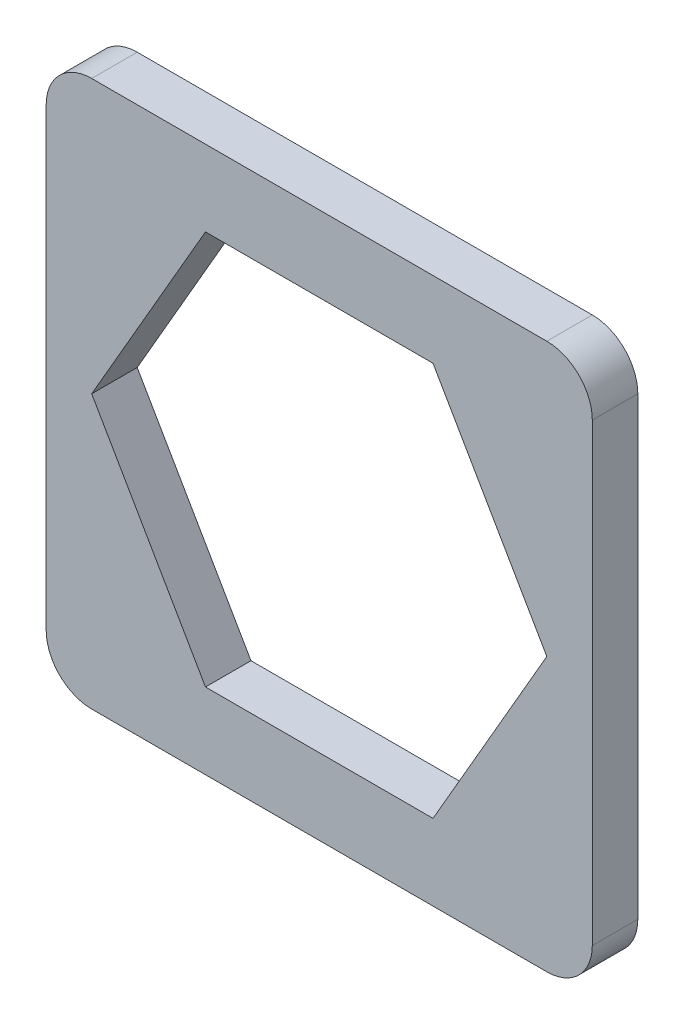
SolidWorks part; units mm, degrees
ref_plane "Front Plane" through (0, 0, 0) normal (0, 0, 1) x (1, 0, 0)
ref_plane "Top Plane" through (0, 0, 0) normal (0, 1, 0) x (1, 0, 0)
ref_plane "Right Plane" through (0, 0, 0) normal (1, 0, 0) x (0, 0, -1)
sketch "Sketch1" plane through (0, 0, 0) normal (0, 0, 1) x (1, 0, 0)
  line L1 (-50, 60) -> (50, 60)
  line L2 (-60, 50) -> (-60, -50)
  line L3 (-50, -60) -> (50, -60)
  line L4 (60, 50) -> (60, -50)
  line L5 (-60, 60) -> (60, -60) construction
  line L6 (-60, -60) -> (60, 60) construction
  arc A0 (-60, -50) -> (-50, -60) centre (-50, -50) ccw
  arc A1 (50, -60) -> (60, -50) centre (50, -50) ccw
  arc A2 (50, 60) -> (60, 50) centre (50, 50) cw
  arc A3 (-50, 60) -> (-60, 50) centre (-50, 50) ccw
  point P0 (0, 0)
  dimension "D3" = 10
  dimension "D1" = 120
  dimension "D2" = 120
extrude "Boss-Extrude1" add sketch "Sketch1" along normal blind 10 contours A3 L2 A0 L3 A1 L4 A2 L1
sketch "Sketch2" plane through (0, 0, 10) normal (0, 0, 1) x (1, 0, 0)
  line L0 (0, 0) -> (0, 40) construction
  line L1 (-50, 50) -> (50, 50) construction
  line L2 (-50, 50) -> (-50, -50) construction
  line L3 (-50, -50) -> (50, -50) construction
  line L4 (50, 50) -> (50, -50) construction
  line L5 (-50, 50) -> (50, -50) construction
  line L6 (-50, -50) -> (50, 50) construction
  line L7 (0, 40) -> (-40, 40) construction
  line L8 (-40, 40) -> (-40, 0) construction
  line L9 (-40, 0) -> (0, 0) construction
  line L11 (0, 20) -> (-20, 20) construction
  line L12 (-20, 40) -> (-20, 20) construction
  circle A0 centre (0, 40) radius 4 construction
  circle A1 centre (0, 20) radius 4 construction
  circle A2 centre (0, 0) radius 4 construction
  circle A3 centre (-20, 20) radius 4 construction
  circle A4 centre (-20, 40) radius 4 construction
  circle A5 centre (-40, 40) radius 4 construction
  circle A6 centre (0, 0) radius 4 construction
  circle A7 centre (20, 0) radius 4 construction
  circle A8 centre (40, 0) radius 4 construction
  circle A9 centre (40, 20) radius 4 construction
  circle A10 centre (40, 40) radius 4 construction
  circle A11 centre (20, 20) radius 4 construction
  circle A12 centre (0, 0) radius 4 construction
  circle A13 centre (0, -20) radius 4 construction
  circle A14 centre (0, -40) radius 4 construction
  circle A15 centre (20, -40) radius 4 construction
  circle A16 centre (40, -40) radius 4 construction
  circle A17 centre (20, -20) radius 4 construction
  circle A18 centre (0, 0) radius 4
  circle A19 centre (-20, 0) radius 4 construction
  circle A20 centre (-40, 0) radius 4 construction
  circle A21 centre (-40, -20) radius 4 construction
  circle A22 centre (-40, -40) radius 4 construction
  circle A23 centre (-20, -20) radius 4 construction
  point P0 (0, 0)
  point P55 (0, 0)
  dimension "D4" = 8
  dimension "D1" = 100
  dimension "D2" = 100
  dimension "D3" = 40
  dimension "D5" = 4
sketch "Sketch3" plane through (0, 0, 10) normal (0, 0, 1) x (1, 0, 0)
  line L0 (-50, -50) -> (50, -50) construction
  line L1 (25, -43.3013) -> (50, 0)
  line L2 (50, 0) -> (25, 43.3013)
  line L3 (25, 43.3013) -> (-25, 43.3013)
  line L4 (-25, 43.3013) -> (-50, 0)
  line L5 (-50, 0) -> (-25, -43.3013)
  line L6 (-25, -43.3013) -> (25, -43.3013)
  circle A0 centre (0, 0) radius 43.3013 construction
  dimension "D1" = 100
extrude "Cut-Extrude3" cut sketch "Sketch3" against normal blind 10
